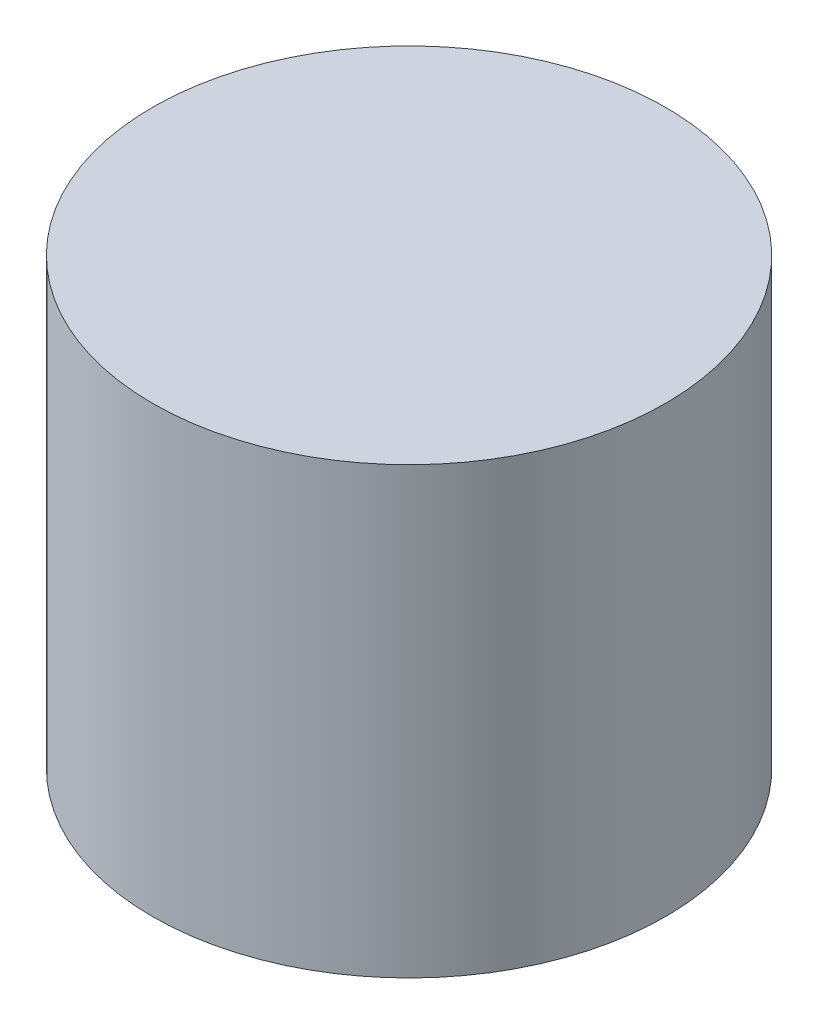
SolidWorks part; units mm, degrees
ref_plane "Front Plane" through (0, 0, 0) normal (0, 0, 1) x (1, 0, 0)
ref_plane "Top Plane" through (0, 0, 0) normal (0, 1, 0) x (1, 0, 0)
ref_plane "Right Plane" through (0, 0, 0) normal (1, 0, 0) x (0, 0, -1)
sketch "Sketch1" plane through (0, 0, 0) normal (0, 1, 0) x (1, 0, 0)
  circle A0 centre (0, 0) radius 75
  dimension "D1" = 150
extrude "Boss-Extrude1" add sketch "Sketch1" along normal blind 130
